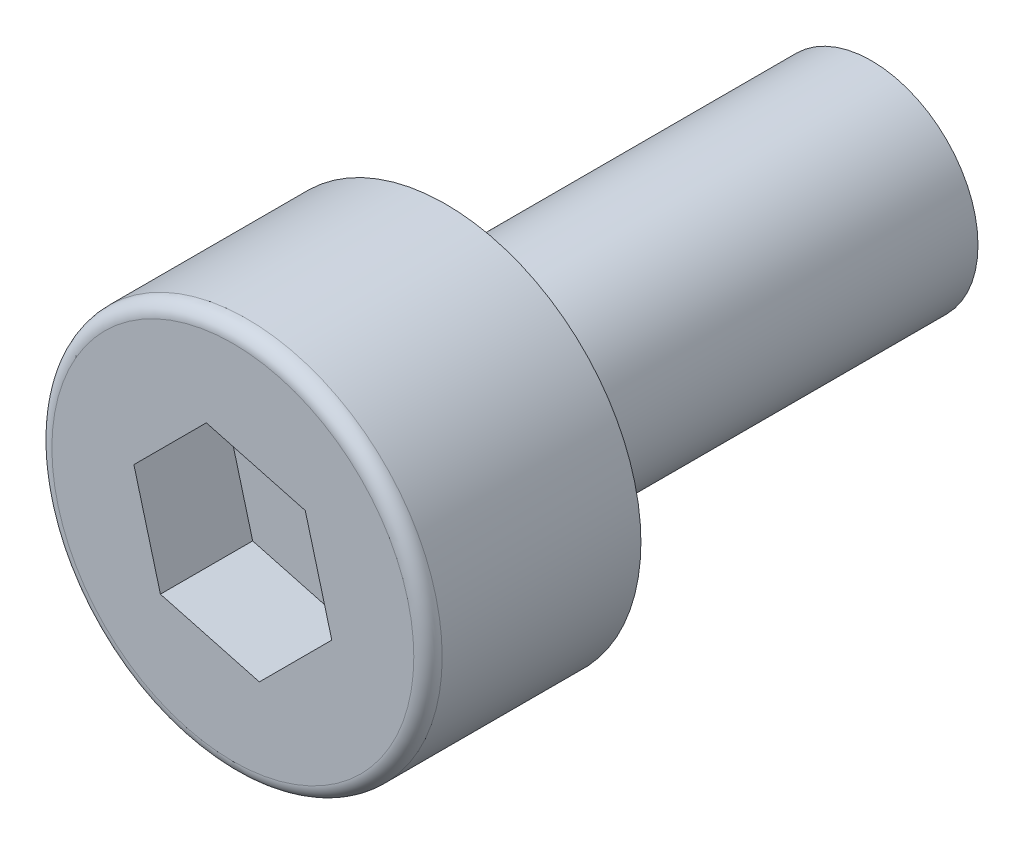
SolidWorks part; units mm, degrees
ref_plane "前视基准面" through (0, 0, 0) normal (0, 0, 1) x (1, 0, 0)
ref_plane "上视基准面" through (0, 0, 0) normal (0, 1, 0) x (1, 0, 0)
ref_plane "右视基准面" through (0, 0, 0) normal (1, 0, 0) x (0, 0, -1)
sketch "草图1" plane through (0, 0, 0) normal (0, 0, 1) x (1, 0, 0)
  circle A0 centre (0, 0) radius 2.75
  dimension "D1" = 5.5
extrude "凸台-拉伸1" add sketch "草图1" along normal blind 3
sketch "草图2" plane through (0, 0, 3) normal (0, 0, 1) x (1, 0, 0)
  line L1 (-1.0206, -1.0206) -> (0.3736, -1.3942)
  line L2 (0.3736, -1.3942) -> (1.3942, -0.3736)
  line L3 (1.3942, -0.3736) -> (1.0206, 1.0206)
  line L4 (1.0206, 1.0206) -> (-0.3736, 1.3942)
  line L5 (-0.3736, 1.3942) -> (-1.3942, 0.3736)
  line L6 (-1.3942, 0.3736) -> (-1.0206, -1.0206)
  circle A0 centre (0, 0) radius 1.25 construction
  dimension "D1" = 2.5
extrude "切除-拉伸1" cut sketch "草图2" against normal blind 1.3
sketch "草图3" plane through (0, 0, 0) normal (0, 0, -1) x (-1, 0, 0)
  circle A0 centre (0, 0) radius 1.5
  dimension "D1" = 3
extrude "凸台-拉伸2" add sketch "草图3" along normal blind 6
fillet "圆角1" radius 0.2 1 edges at (2.75, 0, 3)
